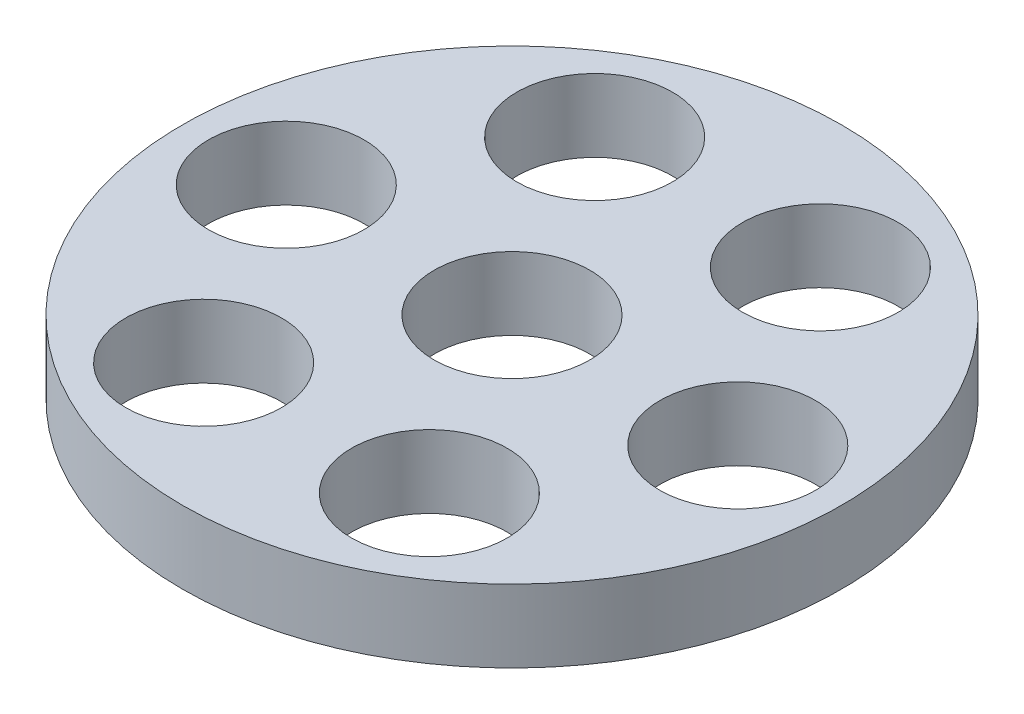
SolidWorks part; units mm, degrees
material "1.0401 (C15)"
ref_plane "Plano frontal" through (0, 0, 0) normal (0, 0, 1) x (1, 0, 0)
ref_plane "Plano superior" through (0, 0, 0) normal (0, 1, 0) x (1, 0, 0)
ref_plane "Plano direito" through (0, 0, 0) normal (1, 0, 0) x (0, 0, -1)
sketch "Esboço1" plane through (0, 0, 0) normal (0, 1, 0) x (1, 0, 0)
  circle A0 centre (0, 0) radius 31.75
  dimension "D1" = 63.5
extrude "Ressalto-extrusão1" add sketch "Esboço1" against normal blind 7
sketch "Esboço2" plane through (0, 0, 0) normal (0, 1, 0) x (1, 0, 0)
  circle A0 centre (0, 0) radius 31.75
  circle A1 centre (0, 0) radius 21.75
  circle A3 centre (0, 0) radius 7.5
  circle A4 centre (21.75, 0) radius 7.5
  circle A5 centre (0.0005, 0.0009) radius 7.5
  circle A6 centre (10.8755, -18.8352) radius 7.5
  circle A7 centre (0.0015, 0.0009) radius 7.5
  circle A8 centre (-10.8735, -18.8352) radius 7.5
  circle A9 centre (0.002, 0) radius 7.5
  circle A10 centre (-21.748, 0) radius 7.5
  circle A11 centre (0.0015, -0.0009) radius 7.5
  circle A12 centre (-10.8735, 18.8352) radius 7.5
  circle A13 centre (0.0005, -0.0009) radius 7.5
  circle A14 centre (10.8755, 18.8352) radius 7.5
  point P29 (0.001, 0)
  dimension "D1" = 63.5
  dimension "D2" = 43.5
  dimension "D3" = 2
  dimension "D4" = 15
  dimension "D5" = 6
extrude "Corte-extrusão1" cut sketch "Esboço2" against normal blind 10 contours A1 A10 | A1 A10 | A1 A12 | A1 A12 | A1 A14 | A1 A14 | A1 A4 | A1 A4 | A1 A6 | A1 A6 | A1 A8 | A1 A8 | A11
